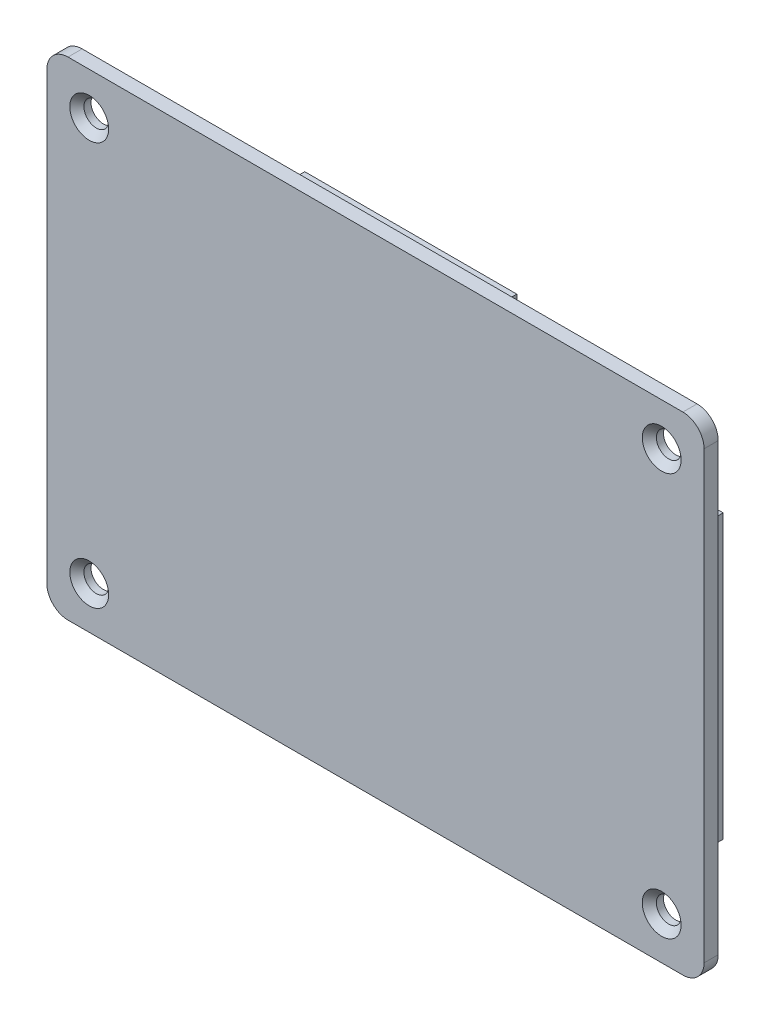
SolidWorks part; units mm, degrees
ref_plane "Front Plane" through (0, 0, 0) normal (0, 0, 1) x (1, 0, 0)
ref_plane "Top Plane" through (0, 0, 0) normal (0, 1, 0) x (1, 0, 0)
ref_plane "Right Plane" through (0, 0, 0) normal (1, 0, 0) x (0, 0, -1)
sketch "Sketch1" plane through (0, 0, 0) normal (0, 0, 1) x (1, 0, 0)
  line L0 (65.2305, -85.7531) -> (65.2305, -22.7531) construction
  line L1 (-24.7695, -88.7531) -> (62.2305, -88.7531) construction
  line L2 (-27.7695, -22.7531) -> (-27.7695, -85.7531) construction
  line L3 (62.2305, -19.7531) -> (-24.7695, -19.7531) construction
  line L4 (65.2305, -85.7531) -> (65.2305, -22.7531)
  line L5 (-24.7695, -88.7531) -> (62.2305, -88.7531)
  line L6 (-27.7695, -22.7531) -> (-27.7695, -85.7531)
  line L7 (62.2305, -19.7531) -> (-24.7695, -19.7531)
  arc A0 (65.2305, -22.7531) -> (62.2305, -19.7531) centre (62.2305, -22.7531) ccw construction
  arc A1 (62.2305, -88.7531) -> (65.2305, -85.7531) centre (62.2305, -85.7531) ccw construction
  arc A2 (-27.7695, -85.7531) -> (-24.7695, -88.7531) centre (-24.7695, -85.7531) ccw construction
  arc A3 (-24.7695, -19.7531) -> (-27.7695, -22.7531) centre (-24.7695, -22.7531) ccw construction
  arc A4 (65.2305, -22.7531) -> (62.2305, -19.7531) centre (62.2305, -22.7531) ccw
  arc A5 (62.2305, -88.7531) -> (65.2305, -85.7531) centre (62.2305, -85.7531) ccw
  arc A6 (-27.7695, -85.7531) -> (-24.7695, -88.7531) centre (-24.7695, -85.7531) ccw
  arc A7 (-24.7695, -19.7531) -> (-27.7695, -22.7531) centre (-24.7695, -22.7531) ccw
extrude "Boss-Extrude1" add sketch "Sketch1" along normal blind 2
sketch "Sketch3" plane through (0, 0, 0) normal (0, 0, -1) x (-1, 0, 0)
  line L1 (-62.9305, -74.2531) -> (-60.9305, -74.2531)
  line L2 (-62.9305, -74.2531) -> (-62.9305, -34.2531)
  line L3 (-62.9305, -34.2531) -> (-60.9305, -34.2531)
  line L4 (-60.9305, -74.2531) -> (-60.9305, -34.2531)
  line L6 (-63.2305, -86.7531) -> (-63.2305, -21.7531) construction
  line L7 (27.7695, -54.2531) -> (-65.2305, -54.2531) construction
  line L8 (27.7695, -22.7531) -> (27.7695, -85.7531) construction
  line L9 (-65.2305, -85.7531) -> (-65.2305, -22.7531) construction
  line L10 (-18.7305, -88.7531) -> (-18.7305, -19.7531) construction
  line L11 (24.7695, -88.7531) -> (-62.2305, -88.7531) construction
  line L12 (-62.2305, -19.7531) -> (24.7695, -19.7531) construction
  line L13 (23.4695, -74.2531) -> (23.4695, -34.2531)
  line L14 (25.4695, -34.2531) -> (23.4695, -34.2531)
  line L15 (25.4695, -74.2531) -> (25.4695, -34.2531)
  line L16 (25.4695, -74.2531) -> (23.4695, -74.2531)
  line L17 (-63.2305, -21.7531) -> (25.7695, -21.7531) construction
  line L18 (-33.7305, -24.0531) -> (-3.7305, -24.0531)
  line L19 (-33.7305, -24.0531) -> (-33.7305, -22.0531)
  line L20 (-33.7305, -22.0531) -> (-3.7305, -22.0531)
  line L21 (-3.7305, -24.0531) -> (-3.7305, -22.0531)
  line L22 (-33.7305, -24.0531) -> (-3.7305, -22.0531) construction
  line L23 (-33.7305, -22.0531) -> (-3.7305, -24.0531) construction
  line L24 (-33.7305, -86.4531) -> (-3.7305, -84.4531) construction
  line L25 (-33.7305, -84.4531) -> (-3.7305, -86.4531) construction
  line L26 (-3.7305, -84.4531) -> (-3.7305, -86.4531)
  line L27 (-33.7305, -86.4531) -> (-3.7305, -86.4531)
  line L28 (-33.7305, -84.4531) -> (-33.7305, -86.4531)
  line L29 (-33.7305, -84.4531) -> (-3.7305, -84.4531)
  point P4 (-62.9305, -54.2531)
  point P23 (-18.7305, -23.0531)
  point P34 (-18.7305, -85.4531)
  dimension "D1" = 2
  dimension "D2" = 40
  dimension "D3" = 2
  dimension "D4" = 0.3
  dimension "D5" = 30
  dimension "D6" = 0.3
extrude "Boss-Extrude2" add sketch "Sketch3" along normal blind 3
sketch "Sketch4" plane through (0, 0, 0) normal (0, 0, -1) x (-1, 0, 0)
  line L0 (21.3195, -25.7031) -> (22.2195, -25.7031) construction
  circle A0 centre (-59.2305, -25.7531) radius 1.75
  circle A1 centre (21.7695, -25.7031) radius 1.75
  circle A2 centre (21.7695, -82.7531) radius 1.75
  circle A3 centre (-59.2305, -82.7531) radius 1.75
  dimension "D1" = 3.5
  dimension "D2" = 3.5
  dimension "D3" = 3.5
  dimension "D4" = 3.5
extrude "Cut-Extrude1" cut sketch "Sketch4" against normal blind 3
chamfer "Chamfer1" distance 1 angle 45 4 edges at (60.9805, -82.7531, 2) (60.9805, -25.7531, 2) (-20.0195, -82.7531, 2) (-20.0195, -25.7031, 2)
